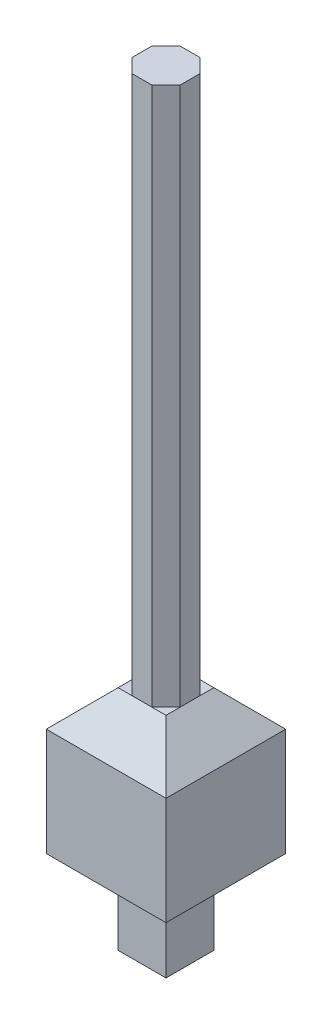
SolidWorks part; units mm, degrees
ref_plane "Front Plane" through (0, 0, 0) normal (0, 0, 1) x (1, 0, 0)
ref_plane "Top Plane" through (0, 0, 0) normal (0, 1, 0) x (1, 0, 0)
ref_plane "Right Plane" through (0, 0, 0) normal (1, 0, 0) x (0, 0, -1)
sketch "Sketch5" plane through (0, 0, 0) normal (0, 1, 0) x (1, 0, 0)
  line L1 (-5, -5) -> (5, -5)
  line L2 (-5, -5) -> (-5, 5)
  line L3 (-5, 5) -> (5, 5)
  line L4 (5, -5) -> (5, 5)
  line L5 (-5, -5) -> (5, 5) construction
  line L6 (-5, 5) -> (5, -5) construction
  point P0 (0, 0)
extrude "Boss-Extrude6" add sketch "Sketch5" along normal blind 8
chamfer "Chamfer10" distance 3 angle 45 4 edges at (0, 0, 5) (5, 0, 0) (0, 0, -5) (-5, 0, 0)
sketch "Sketch6" plane through (0, 0, 0) normal (0, 1, 0) x (1, 0, 0)
  line L0 (2, -2) -> (2, 2)
  line L1 (2, 2) -> (-2, 2)
  line L2 (-2, 2) -> (-2, -2)
  line L3 (2, -2) -> (-2, -2) construction
  line L4 (-2, -2) -> (2, -2)
extrude "Boss-Extrude7" add sketch "Sketch6" against normal blind 4
ref_plane "Plane2" through (0, 8, 0) normal (0, 1, 0) x (1, 0, 0)
sketch "Sketch7" plane through (0, 8, 0) normal (0, 1, 0) x (1, 0, 0)
  line L0 (-5, 5) -> (-5, -5) construction
  line L1 (5, -5) -> (-5, -5)
  line L2 (5, -5) -> (5, 5)
  line L3 (5, 5) -> (-5, 5)
  line L4 (-5, -5) -> (-5, 5)
  line L5 (5, -5) -> (-5, 5) construction
  line L6 (5, 5) -> (-5, -5) construction
  line L7 (5, 5) -> (-5, 5) construction
  point P0 (0, 0)
extrude "Boss-Extrude9" add sketch "Sketch7" along normal blind 7
chamfer "Chamfer13" distance 3 angle 45 4 edges at (-5, 15, 0) (0, 15, -5) (5, 15, 0) (0, 15, 5)
ref_plane "Plane3" through (0, 15, 0) normal (0, 1, 0) x (1, 0, 0)
sketch "Sketch8" plane through (0, 15, 0) normal (0, 1, 0) x (1, 0, 0)
  line L1 (2, 0.8284) -> (0.8284, 2)
  line L2 (0.8284, 2) -> (-0.8284, 2)
  line L3 (-0.8284, 2) -> (-2, 0.8284)
  line L4 (-2, 0.8284) -> (-2, -0.8284)
  line L5 (-2, -0.8284) -> (-0.8284, -2)
  line L6 (-0.8284, -2) -> (0.8284, -2)
  line L7 (0.8284, -2) -> (2, -0.8284)
  line L8 (2, -0.8284) -> (2, 0.8284)
  circle A0 centre (0, 0) radius 2 construction
extrude "Boss-Extrude11" add sketch "Sketch8" along normal blind 45
